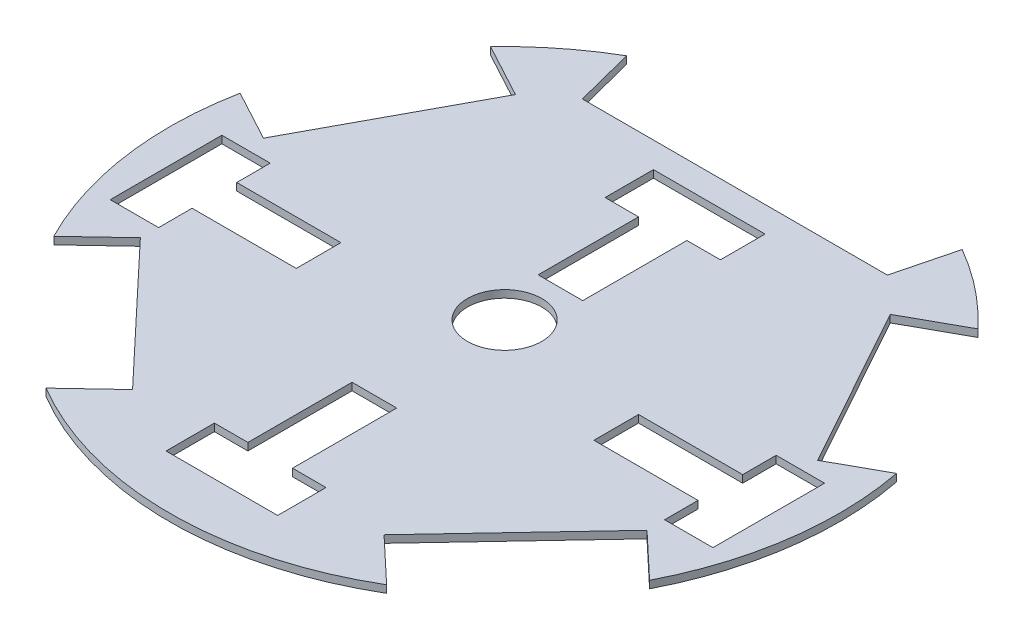
SolidWorks part; units mm, degrees
ref_plane "Front Plane" through (0, 0, 0) normal (0, 0, 1) x (1, 0, 0)
ref_plane "Top Plane" through (0, 0, 0) normal (0, 1, 0) x (1, 0, 0)
ref_plane "Right Plane" through (0, 0, 0) normal (1, 0, 0) x (0, 0, -1)
sketch "Sketch1" plane through (0, 0, 0) normal (0, 1, 0) x (1, 0, 0)
  line L0 (-68, -4) -> (-40, -4)
  line L10 (-68, -16) -> (-40, -16)
  line L11 (-40, -4) -> (-40, -16)
  line L12 (-81, 5) -> (-68, 5)
  line L13 (-81, 5) -> (-81, -25)
  line L14 (-81, -25) -> (-68, -25)
  line L60 (62.6306, 31.2635) -> (80.5251, 40.1959)
  line L61 (65.4975, -61.7259) -> (50.9425, -48.009)
  line L62 (50.9425, -48.009) -> (68.0885, -29.8153)
  line L63 (50.9425, -48.009) -> (33.7964, -66.2027)
  line L64 (68.0885, -29.8153) -> (80.0659, -41.1029)
  line L65 (33.7964, -66.2027) -> (45.7738, -77.4904)
  line L66 (-62.8715, 31.9168) -> (-51.0135, 53.9256)
  line L67 (-62.8715, 31.9168) -> (-74.7295, 9.908)
  line L68 (-80.2513, 40.7397) -> (-62.8715, 31.9168)
  line L69 (-51.0135, 53.9256) -> (-65.4953, 61.7282)
  line L70 (-74.7295, 9.908) -> (-88.3338, 17.2378)
  line L71 (62.6306, 31.2635) -> (74.7508, 9.398)
  line L72 (62.6306, 31.2635) -> (50.5104, 53.129)
  line L73 (50.5104, 53.129) -> (65.6763, 61.5356)
  line L74 (74.7508, 9.398) -> (88.3881, 16.9572)
  line L75 (-65.4975, -61.7259) -> (-50.9425, -48.009)
  line L76 (-50.9425, -48.009) -> (-33.7964, -66.2027)
  line L77 (-50.9425, -48.009) -> (-68.0885, -29.8153)
  line L78 (-68.0885, -29.8153) -> (-80.0659, -41.1029)
  line L79 (-33.7964, -66.2027) -> (-45.7738, -77.4904)
  line L80 (-45.0961, 77.8867) -> (-41, 61.8867)
  line L81 (0, 61.8867) -> (-41, 61.8867)
  line L82 (0, 61.8867) -> (41, 61.8867)
  line L83 (45.0961, 77.8867) -> (41, 61.8867)
  line L84 (-68, -16) -> (-68, -25)
  line L85 (-68, 5) -> (-68, -4)
  line L86 (68, -16) -> (40, -16)
  line L87 (67.9909, -4) -> (40, -4)
  line L88 (40, -16) -> (40, -4)
  line L89 (80.9909, -25) -> (68, -25)
  line L90 (80.9909, -25) -> (80.9909, 5)
  line L91 (80.9909, 5) -> (67.9909, 5)
  line L92 (67.9909, -4) -> (67.9909, 5)
  line L93 (68, -25) -> (68, -16)
  line L94 (6, 43) -> (6, 15)
  line L95 (-6, 42) -> (-6, 15)
  line L96 (6, 15) -> (-6, 15)
  line L97 (15, 55) -> (15, 43)
  line L98 (15, 55) -> (-15, 55)
  line L99 (-15, 55) -> (-15, 42)
  line L100 (-6, 42) -> (-15, 42)
  line L101 (15, 43) -> (6, 43)
  line L102 (-6, -63) -> (-6, -35)
  line L103 (6, -63) -> (6, -35)
  line L104 (-6, -35) -> (6, -35)
  line L105 (-15, -76) -> (-15, -63)
  line L106 (-15, -76) -> (15, -76)
  line L107 (15, -76) -> (15, -63)
  line L108 (6, -63) -> (15, -63)
  line L109 (-15, -63) -> (-6, -63)
  line L110 (0, 15) -> (0, 0) construction
  line L111 (0, -35) -> (0, 0) construction
  line L112 (-40, -10) -> (40, -10) construction
  circle A0 centre (0, 0) radius 90
  circle A23 centre (0, 0) radius 10
  dimension "D17" = 12
  dimension "D19" = 180
  dimension "D29" = 20
  dimension "D3" = 40
  dimension "D4" = 9
  dimension "D5" = 28
  dimension "D6" = 12
  dimension "D7" = 9
  dimension "D8" = 9
  dimension "D9" = 28
  dimension "D10" = 12
  dimension "D11" = 9
  dimension "D12" = 28
  dimension "D13" = 9
  dimension "D14" = 15
  dimension "D15" = 12
  dimension "D16" = 28
  dimension "13" = 13
  dimension "D18" = 16
  dimension "D20" = 9
  dimension "D21" = 9
  dimension "D22" = 10
  dimension "D23" = 40
  dimension "D24" = 13
  dimension "D25" = 35
  dimension "D26" = 13
  dimension "D27" = 13
  dimension "D28" = 28
extrude "Boss-Extrude1" add sketch "Sketch1" along normal blind 2
